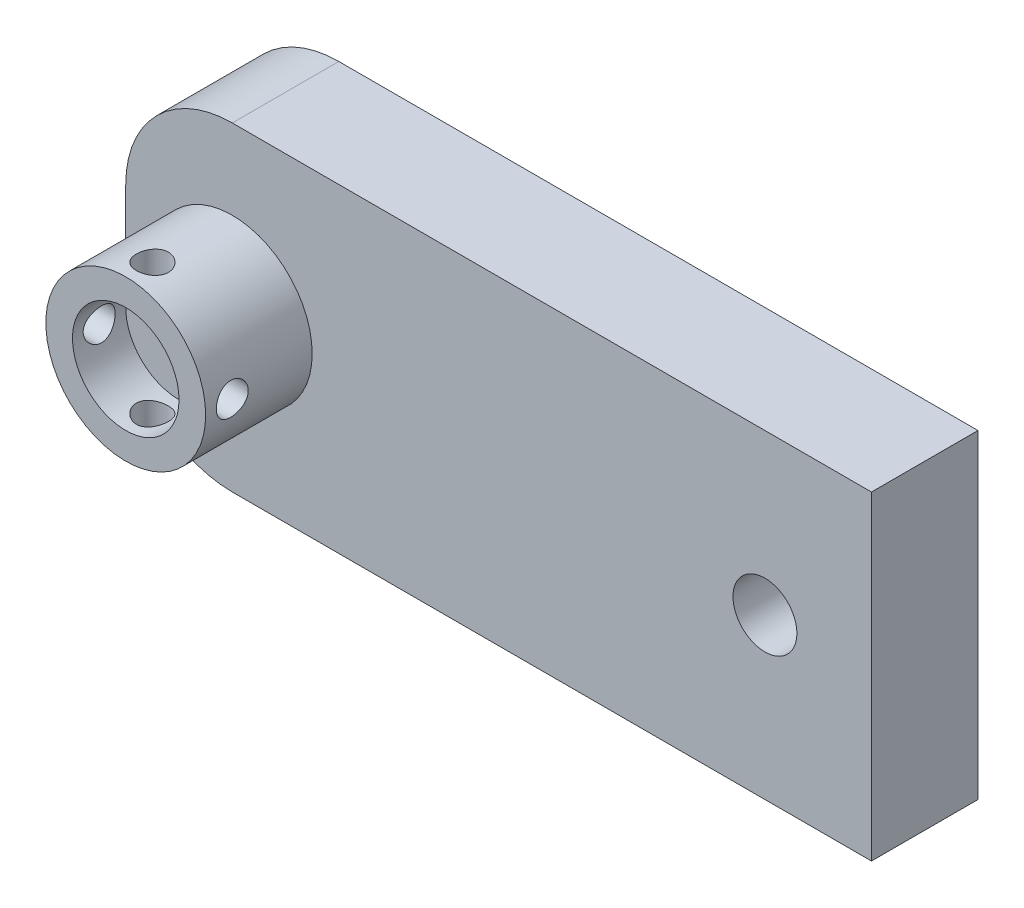
SolidWorks part; units mm, degrees
ref_plane "Front Plane" through (0, 0, 0) normal (0, 0, 1) x (1, 0, 0)
ref_plane "Top Plane" through (0, 0, 0) normal (0, 1, 0) x (1, 0, 0)
ref_plane "Right Plane" through (0, 0, 0) normal (1, 0, 0) x (0, 0, -1)
sketch "Sketch1" plane through (0, 0, 0) normal (0, 0, 1) x (1, 0, 0)
  line L0 (-41.4361, 5.7181) -> (-41.4361, -4.2819)
  line L1 (28.5639, -14.2819) -> (-31.4361, -14.2819)
  line L2 (28.5639, -14.2819) -> (28.5639, 15.7181)
  line L3 (28.5639, 15.7181) -> (-31.4361, 15.7181)
  line L5 (28.5639, -14.2819) -> (-31.4361, 15.7181) construction
  line L6 (28.5639, 15.7181) -> (-34.6135, -19.0471) construction
  arc A0 (-31.4361, -14.2819) -> (-41.4361, -4.2819) centre (-31.4361, -4.2819) cw
  arc A1 (-31.4361, 15.7181) -> (-41.4361, 5.7181) centre (-31.4361, 5.7181) ccw
  point P0 (0, 0)
  dimension "D3" = 10
  dimension "D1" = 60
  dimension "D2" = 30
extrude "Boss-Extrude1" add sketch "Sketch1" along normal blind 10 contours L3 A1 L0 A0 L1 L2
sketch "Sketch2" plane through (0, 0, 0) normal (0, 0, 1) x (1, 0, 0)
  line L0 (-31.4361, 15.7181) -> (-31.4361, -14.2819) construction
  point P4 (-31.4361, 0.7181)
sketch "Sketch5" plane through (0, 0, 0) normal (0, 0, -1) x (-1, 0, 0)
  line L0 (31.4361, 0.7181) -> (-8.5639, 0.7181) construction
  line L1 (31.4361, 15.7181) -> (31.4361, -14.2819) construction
  dimension "D1" = 40
sketch "Sketch6" plane through (0, 0, 0) normal (0, 0, -1) x (-1, 0, 0)
  line L0 (31.4361, 0.7181) -> (-8.5639, 0.7181) construction
  line L1 (5.4361, -11.7819) -> (-24.5639, -11.7819)
  line L2 (5.4361, -11.7819) -> (5.4361, 13.2181)
  line L3 (5.4361, 13.2181) -> (-24.5639, 13.2181)
  line L4 (-24.5639, -11.7819) -> (-24.5639, 13.2181)
  line L5 (5.4361, -11.7819) -> (-24.5639, 13.2181) construction
  line L6 (5.4361, 13.2181) -> (-24.5639, -11.7819) construction
  line L7 (-28.5639, -14.2819) -> (-28.5639, 15.7181) construction
  point P0 (-9.5639, 0.7181)
  dimension "D1" = 4
  dimension "D2" = 30
  dimension "D3" = 25
extrude "Cut-Extrude1" cut sketch "Sketch6" against normal blind 3
sketch "Sketch7" plane through (0, 0, 10) normal (0, 0, 1) x (1, 0, 0)
  line L0 (-31.4361, 0.7181) -> (18.5639, 0.7181) construction
  dimension "D1" = 50
sketch "Sketch8" plane through (0, 0, 10) normal (0, 0, 1) x (1, 0, 0)
  circle A0 centre (18.5639, 0.7181) radius 3
  dimension "D1" = 6
extrude "Cut-Extrude2" cut sketch "Sketch8" against normal blind 10
sketch "Sketch9" plane through (0, 0, 10) normal (0, 0, 1) x (1, 0, 0)
  circle A0 centre (-31.4361, 0.7181) radius 7.5
  dimension "D1" = 15
extrude "Boss-Extrude2" add sketch "Sketch9" along normal blind 10
sketch "Sketch10" plane through (0, 0, 20) normal (0, 0, 1) x (1, 0, 0)
  circle A0 centre (-31.4361, 0.7181) radius 5
  dimension "D1" = 10
extrude "Cut-Extrude3" cut sketch "Sketch10" against normal blind 5
sketch "Sketch11" plane through (0, 0, 0) normal (0, 1, 0) x (1, 0, 0)
  line L0 (-31.4361, -20) -> (-31.4361, -17.5) construction
  line L1 (-38.9361, -20) -> (-23.9361, -20) construction
  circle A0 centre (-31.4361, -17.5) radius 1.5
  dimension "D2" = 3
  dimension "D1" = 2.5
extrude "Cut-Extrude4" cut sketch "Sketch11" against normal through all both and the other way through all
pattern_circular "CirPattern1" count 2 every 90 about axis through (-31.4361, 0.7181, 20) along (0, 0, -1) of "Cut-Extrude4"
hole_wizard "1/4 (0.25) Diameter Hole1" positions "Sketch12" profile "Sketch13" hole size "1/4" standard "ANSI Inch"
sketch "Sketch12" plane through (0, 0, 0) normal (0, 0, -1) x (-1, 0, 0)
  point P0 (31.4361, 0.7181)
sketch "Sketch13" plane through (-31.4361, 0.7181, 0) normal (1, 0, 0) x (0, 1, 0)
  line L0 (0, 0) -> (0, 11.9077)
  line L1 (0, 11.9077) -> (3.175, 10)
  line L2 (3.175, 10) -> (3.175, 0)
  line L5 (3.175, 0) -> (0, 0)
  line L10 (0, 11.9077) -> (-3.175, 10) construction
  line L11 (0, -6.35) -> (0, 107.95) construction
  dimension "Hole Dia." = 6.35
  dimension "Hole Depth" = 10
  dimension "Drill Angle" = 118
